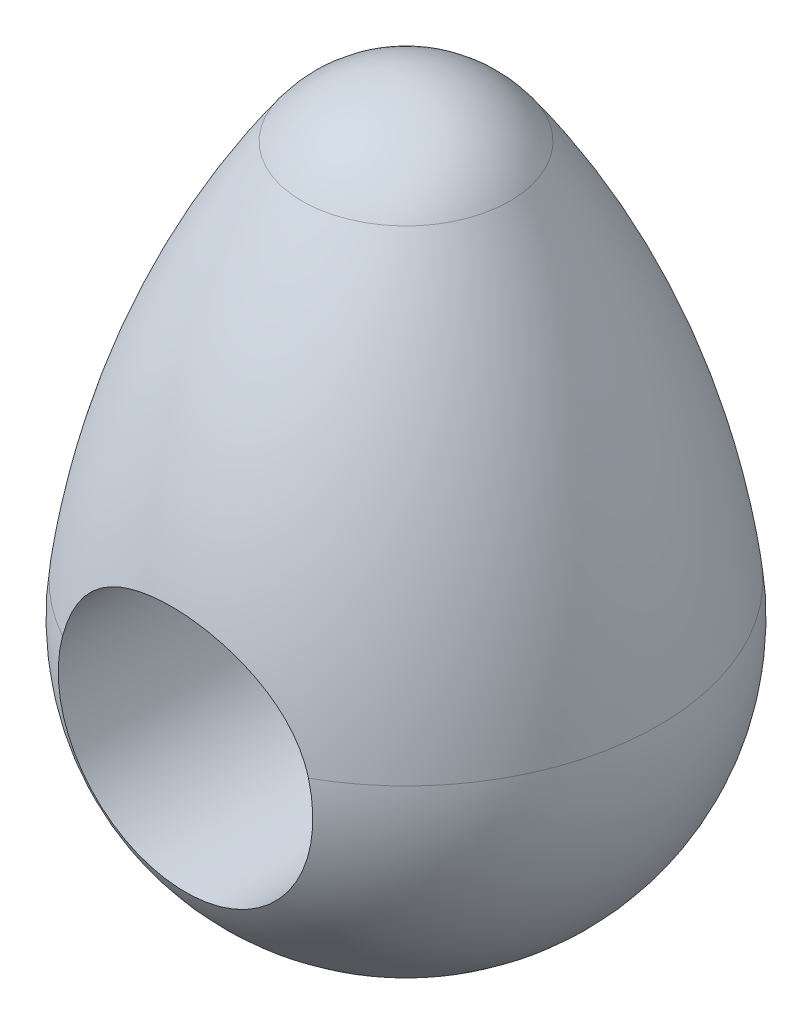
SolidWorks part; units mm, degrees
ref_plane "Front Plane" through (0, 0, 0) normal (0, 0, 1) x (1, 0, 0)
ref_plane "Top Plane" through (0, 0, 0) normal (0, 1, 0) x (1, 0, 0)
ref_plane "Right Plane" through (0, 0, 0) normal (1, 0, 0) x (0, 0, -1)
sketch "Sketch1" plane through (0, 0, 0) normal (0, 0, 1) x (1, 0, 0)
  line L0 (0, 0) -> (0, 88.9)
  line L1 (0, 0) -> (0, -38.1)
  arc A1 (-15.5562, 61.7958) -> (-37.7794, 4.9326) centre (88.1518, -11.5094) ccw
  arc A4 (-15.5562, 61.7958) -> (0, 69.85) centre (0, 50.8) cw
  arc A5 (-37.7794, 4.9326) -> (0, -38.1) centre (0, 0) ccw
  point P9 (0, 0)
  point P10 (0, 0)
  dimension "D1" = 19.05
  dimension "D2" = 127
  dimension "D4" = 50.8
  dimension "D3" = 38.1
revolve "Revolve4" add sketch "Sketch1" angle 360 about L0
sketch "Sketch2" plane through (0, 0, 0) normal (0, 0, 1) x (1, 0, 0)
  circle A0 centre (0, 0) radius 19.05
  dimension "D1" = 38.1
extrude "Cut-Extrude1" cut sketch "Sketch2" against normal through all both and the other way through all
